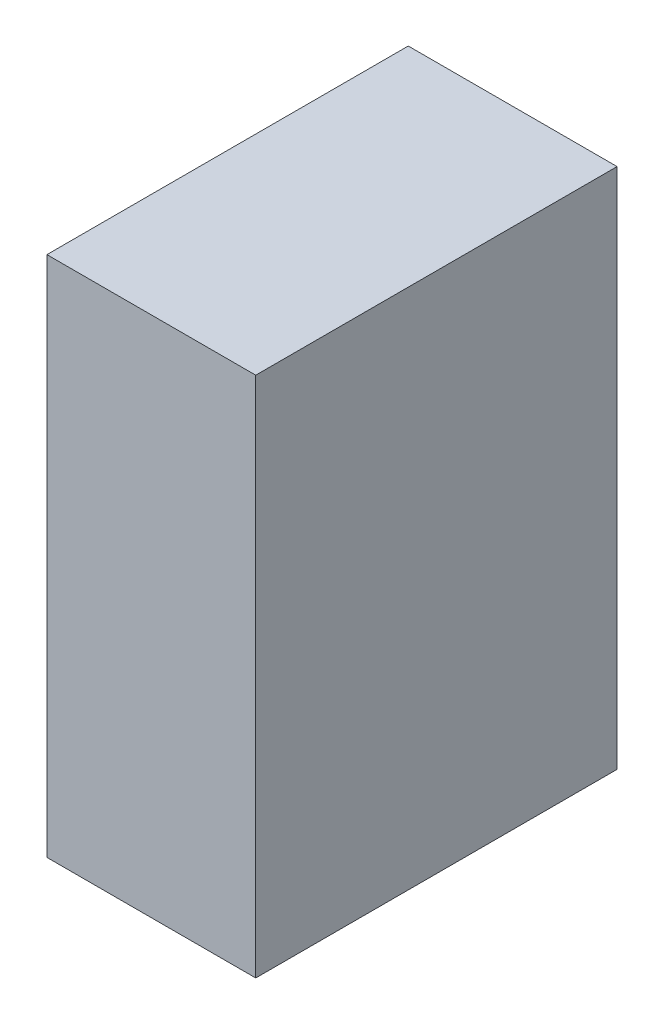
SolidWorks part; units mm, degrees
material "6061 Alloy"
ref_plane "Front Plane" through (0, 0, 0) normal (0, 0, 1) x (1, 0, 0)
ref_plane "Top Plane" through (0, 0, 0) normal (0, 1, 0) x (1, 0, 0)
ref_plane "Right Plane" through (0, 0, 0) normal (1, 0, 0) x (0, 0, -1)
sketch "Sketch1" plane through (0, 0, 0) normal (0, 0, 1) x (1, 0, 0)
  line L1 (-12.7, 31.75) -> (12.7, 31.75)
  line L2 (-12.7, 31.75) -> (-12.7, -31.75)
  line L3 (-12.7, -31.75) -> (12.7, -31.75)
  line L4 (12.7, 31.75) -> (12.7, -31.75)
  line L5 (-12.7, 31.75) -> (12.7, -31.75) construction
  line L6 (-12.7, -31.75) -> (12.7, 31.75) construction
  point P0 (0, 0)
  dimension "D1" = 63.5
  dimension "D2" = 25.4
extrude "Boss-Extrude1" add sketch "Sketch1" along normal blind 43.95
